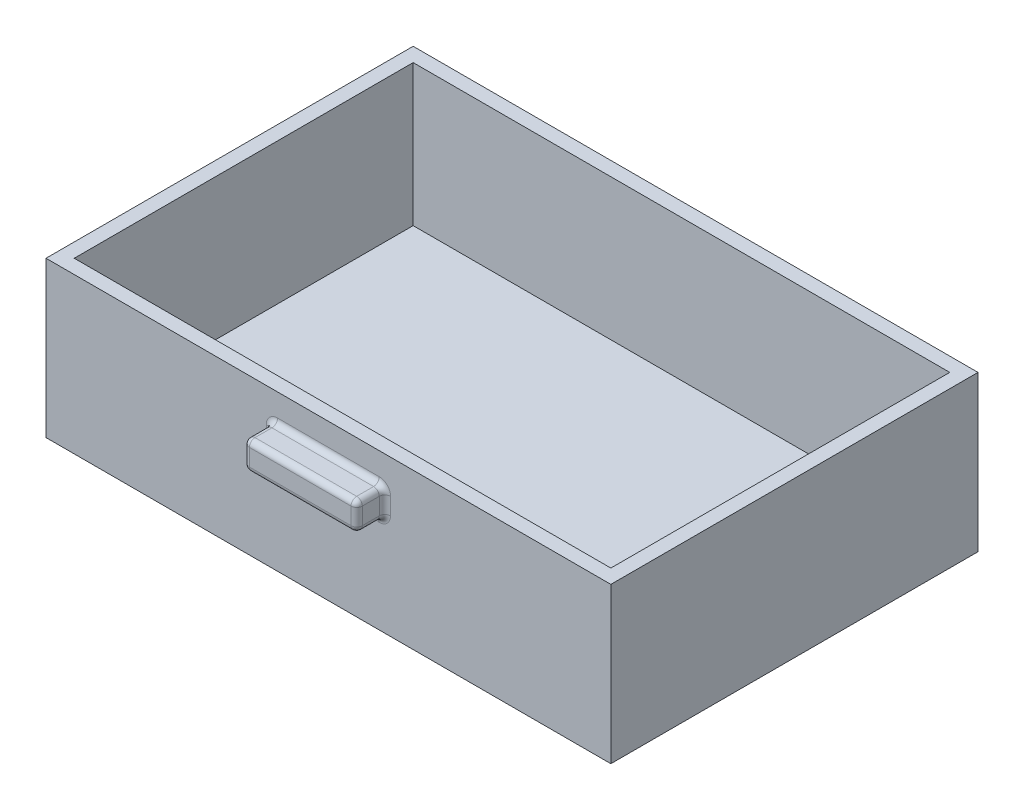
SolidWorks part; units mm, degrees
ref_plane "Front Plane" through (0, 0, 0) normal (0, 0, 1) x (1, 0, 0)
ref_plane "Top Plane" through (0, 0, 0) normal (0, 1, 0) x (1, 0, 0)
ref_plane "Right Plane" through (0, 0, 0) normal (1, 0, 0) x (0, 0, -1)
sketch "Sketch2" plane through (0, 0, 0) normal (0, 1, 0) x (1, 0, 0)
  line L1 (-127, -82.55) -> (127, -82.55)
  line L2 (-127, -82.55) -> (-127, 82.55)
  line L3 (-127, 82.55) -> (127, 82.55)
  line L4 (127, -82.55) -> (127, 82.55)
  line L5 (-127, -82.55) -> (127, 82.55) construction
  line L6 (-127, 82.55) -> (127, -82.55) construction
  point P0 (0, 0)
  dimension "D1" = 165.1
  dimension "D2" = 254
extrude "Boss-Extrude1" add sketch "Sketch2" along normal blind 6.35
sketch "Sketch3" plane through (0, 6.35, 0) normal (0, 1, 0) x (1, 0, 0)
  line L0 (-120.65, -76.2) -> (-120.65, 76.2)
  line L1 (-127, -82.55) -> (127, -82.55)
  line L2 (-127, -82.55) -> (-127, 82.55)
  line L3 (-127, 82.55) -> (127, 82.55)
  line L4 (127, -82.55) -> (127, 82.55)
  line L5 (-120.65, 76.2) -> (120.65, 76.2)
  line L6 (120.65, -76.2) -> (120.65, 76.2)
  line L7 (-120.65, -76.2) -> (120.65, -76.2)
  dimension "D1" = 6.35
extrude "Boss-Extrude2" add sketch "Sketch3" along normal blind 63.5
sketch "Sketch4" plane through (0, 0, 82.55) normal (0, 0, 1) x (1, 0, 0)
  line L0 (-127, 69.85) -> (127, 69.85) construction
  line L1 (-25.4, 57.15) -> (25.4, 57.15)
  line L2 (-25.4, 57.15) -> (-25.4, 44.45)
  line L3 (-25.4, 44.45) -> (25.4, 44.45)
  line L4 (25.4, 57.15) -> (25.4, 44.45)
  line L5 (127, 69.85) -> (127, 0) construction
  point P6 (25.4, 50.8)
  dimension "D1" = 12.7
  dimension "D2" = 50.8
  dimension "D3" = 12.7
  dimension "D4" = 101.6
extrude "Boss-Extrude3" add sketch "Sketch4" along normal blind 12.7
sketch "Sketch6" plane through (0, 44.45, 0) normal (0, -1, 0) x (-1, 0, 0)
  line L0 (25.4, -82.55) -> (-25.4, -82.55) construction
  line L1 (22.225, -82.55) -> (-22.225, -82.55)
  line L2 (22.225, -82.55) -> (22.225, -90.8262)
  line L3 (22.225, -90.8262) -> (-22.225, -90.8262)
  line L4 (-22.225, -82.55) -> (-22.225, -90.8262)
  line L5 (-25.4, -95.25) -> (-25.4, -82.55) construction
  dimension "D1" = 44.45
  dimension "D2" = 3.175
extrude "Cut-Extrude1" cut sketch "Sketch6" against normal blind 8.89
fillet "Fillet1" radius 2.54 13 edges at (23.8125, 44.45, 82.55) (-23.8125, 44.45, 82.55) (25.4, 50.8, 82.55) (-25.4, 50.8, 82.55) (25.4, 57.15, 88.9) (0, 57.15, 95.25) (-25.4, 57.15, 88.9) (0, 57.15, 82.55) (25.4, 44.45, 88.9) (-25.4, 44.45, 88.9) (0, 44.45, 95.25) (25.4, 50.8, 95.25) (-25.4, 50.8, 95.25)
